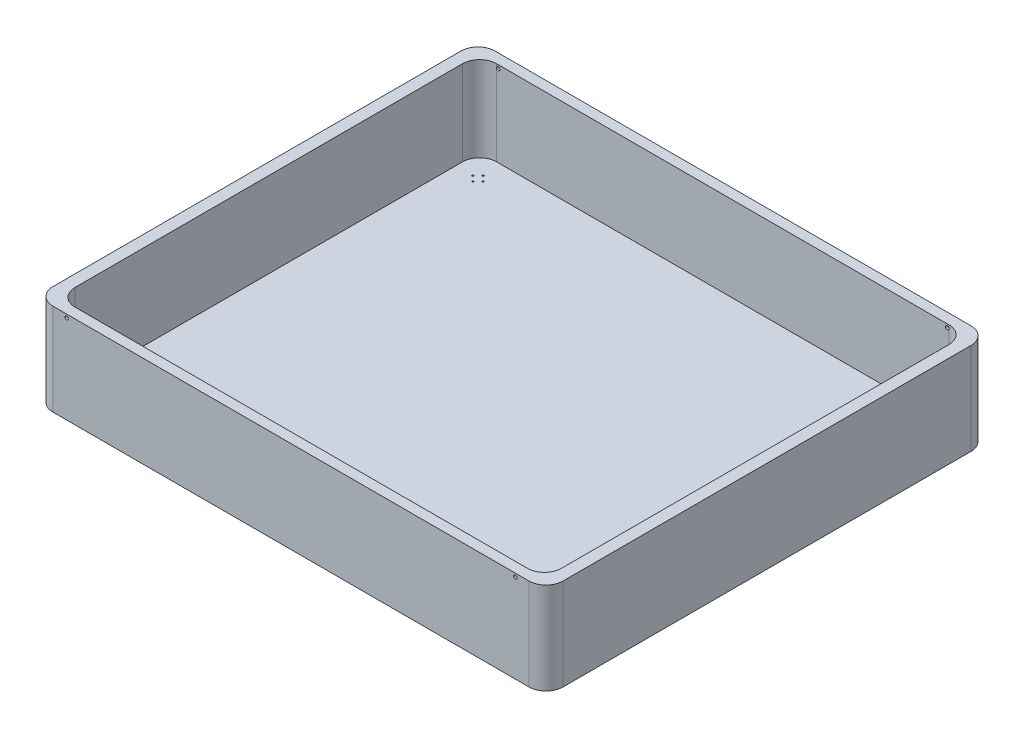
SolidWorks part; units mm, degrees
ref_plane "Спереди" through (0, 0, 0) normal (0, 0, 1) x (1, 0, 0)
ref_plane "Сверху" through (0, 0, 0) normal (0, 1, 0) x (1, 0, 0)
ref_plane "Справа" through (0, 0, 0) normal (1, 0, 0) x (0, 0, -1)
sketch "Эскиз1" plane through (0, 0, 0) normal (0, 1, 0) x (1, 0, 0)
  line L1 (-700, -650) -> (700, -650)
  line L2 (-750, -600) -> (-750, 600)
  line L3 (-700, 650) -> (700, 650)
  line L4 (750, -600) -> (750, 600)
  line L5 (-750, -650) -> (750, 650) construction
  line L6 (-750, 650) -> (750, -650) construction
  arc A0 (-700, -650) -> (-750, -600) centre (-700, -600) cw
  arc A1 (700, -650) -> (750, -600) centre (700, -600) ccw
  arc A2 (700, 650) -> (750, 600) centre (700, 600) cw
  arc A3 (-750, 600) -> (-700, 650) centre (-700, 600) cw
  point P0 (0, 0)
  dimension "D3" = 50
  dimension "D1" = 1300
  dimension "D2" = 1500
extrude "Бобышка-Вытянуть1" add sketch "Эскиз1" along normal blind 20 contours L3 A2 L4 A1 L1 A0 L2 A3
sketch "Эскиз2" plane through (0, 20, 0) normal (0, 1, 0) x (1, 0, 0)
  line L1 (700, -650) -> (-700, -650)
  line L2 (750, -600) -> (750, 600)
  line L3 (700, 650) -> (-700, 650)
  line L4 (-750, -600) -> (-750, 600)
  line L5 (750, -650) -> (-750, 650) construction
  line L6 (750, 650) -> (-750, -650) construction
  line L7 (665.3846, -620) -> (-665.3846, -620)
  line L8 (715.3846, -570) -> (715.3846, 570)
  line L9 (665.3846, 620) -> (-665.3846, 620)
  line L10 (-715.3846, -570) -> (-715.3846, 570)
  line L11 (715.3846, -620) -> (-715.3846, 620) construction
  line L12 (715.3846, 620) -> (-715.3846, -620) construction
  arc A0 (750, 600) -> (700, 650) centre (700, 600) ccw
  arc A1 (700, -650) -> (750, -600) centre (700, -600) ccw
  arc A2 (-700, 650) -> (-750, 600) centre (-700, 600) ccw
  arc A3 (-700, -650) -> (-750, -600) centre (-700, -600) cw
  arc A4 (715.3846, 570) -> (665.3846, 620) centre (665.3846, 570) ccw
  arc A5 (665.3846, -620) -> (715.3846, -570) centre (665.3846, -570) ccw
  arc A6 (-665.3846, -620) -> (-715.3846, -570) centre (-665.3846, -570) cw
  arc A7 (-665.3846, 620) -> (-715.3846, 570) centre (-665.3846, 570) ccw
  point P0 (0, 0)
  point P18 (0, 0)
  dimension "D3" = 50
  dimension "D5" = 50
  dimension "D1" = 1500
  dimension "D2" = 1300
  dimension "D4" = 30
extrude "Бобышка-Вытянуть2" add sketch "Эскиз2" along normal blind 250
sketch "Эскиз3" plane through (0, 0, 0) normal (0, -1, 0) x (1, 0, 0)
  line L0 (-750, 600) -> (-750, -600) construction
  line L1 (-650, -550) -> (650, -550)
  line L2 (-650, -550) -> (-650, 550)
  line L3 (-650, 550) -> (650, 550)
  line L4 (650, -550) -> (650, 550)
  line L5 (-650, -550) -> (650, 550) construction
  line L6 (-650, 550) -> (650, -550) construction
  line L7 (-700, 650) -> (700, 650) construction
  line L8 (0, 0) -> (650, 0) construction
  line L9 (0, 0) -> (0, 550) construction
  circle A0 centre (-650, 550) radius 15
  circle A1 centre (-650, 535) radius 2.5
  circle A2 centre (-665, 550) radius 2.5
  circle A3 centre (-650, 565) radius 2.5
  circle A4 centre (-635, 550) radius 2.5
  circle A5 centre (650, 535) radius 2.5
  circle A6 centre (635, 550) radius 2.5
  circle A7 centre (665, 550) radius 2.5
  circle A8 centre (650, 565) radius 2.5
  circle A9 centre (650, -565) radius 2.5
  circle A10 centre (635, -550) radius 2.5
  circle A11 centre (650, -535) radius 2.5
  circle A12 centre (665, -550) radius 2.5
  circle A13 centre (-635, -550) radius 2.5
  circle A14 centre (-650, -535) radius 2.5
  circle A15 centre (-665, -550) radius 2.5
  circle A16 centre (-650, -565) radius 2.5
  point P1 (0, 0)
  point P22 (-650, 550)
  dimension "D3" = 30
  dimension "D4" = 5
  dimension "D7" = 30
  dimension "D1" = 100
  dimension "D2" = 100
  dimension "D6" = 15
  dimension "D5" = 4
extrude "Вырез-Вытянуть1" cut sketch "Эскиз3" against normal blind 250 contours A16 | A3 | A2 | A4 | A1 | A7 | A8 | A6 | A5 | A11 | A10 | A12 | A9 | A14 | A15 | A13
sketch "Эскиз4" plane through (0, 0, -650) normal (0, 0, -1) x (-1, 0, 0)
  line L0 (700, 0) -> (-700, 0) construction
  line L1 (750, 270) -> (750, 0) construction
  circle A0 centre (660, 260) radius 5
  dimension "D1" = 10
  dimension "D2" = 260
  dimension "D3" = 90
extrude "Вырез-Вытянуть2" cut sketch "Эскиз4" against normal blind 1500
ref_plane "Плоскость1" through (0, 0, 0) normal (-1, 0, 0) x (0, 0, 1)
mirror "Зеркальное отражение1" about plane through (0, 0, 0) normal (-1, 0, 0) of "Вырез-Вытянуть2"
